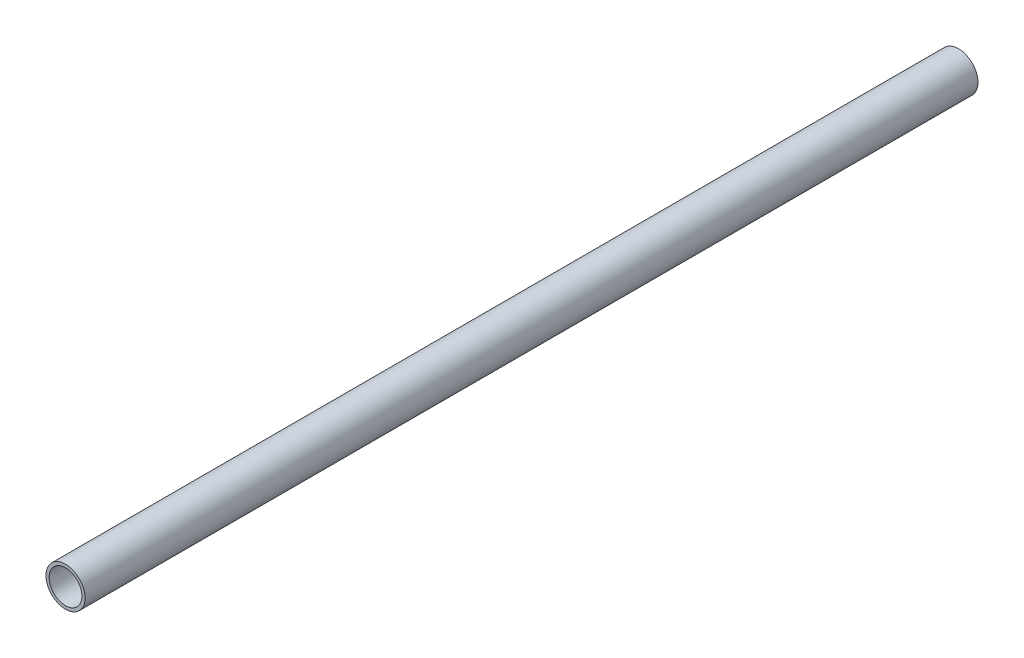
SolidWorks part; units mm, degrees
ref_plane "Alzado" through (0, 0, 0) normal (0, 0, 1) x (1, 0, 0)
ref_plane "Planta" through (0, 0, 0) normal (0, 1, 0) x (1, 0, 0)
ref_plane "Vista lateral" through (0, 0, 0) normal (1, 0, 0) x (0, 0, -1)
sketch "Croquis1" plane through (0, 0, 0) normal (0, 0, 1) x (1, 0, 0)
  circle A0 centre (0, 0) radius 12.5
  circle A1 centre (0, 0) radius 10.5
  dimension "D1" = 25
  dimension "D2" = 2
extrude "Saliente-Extruir1" add sketch "Croquis1" along normal blind 571
